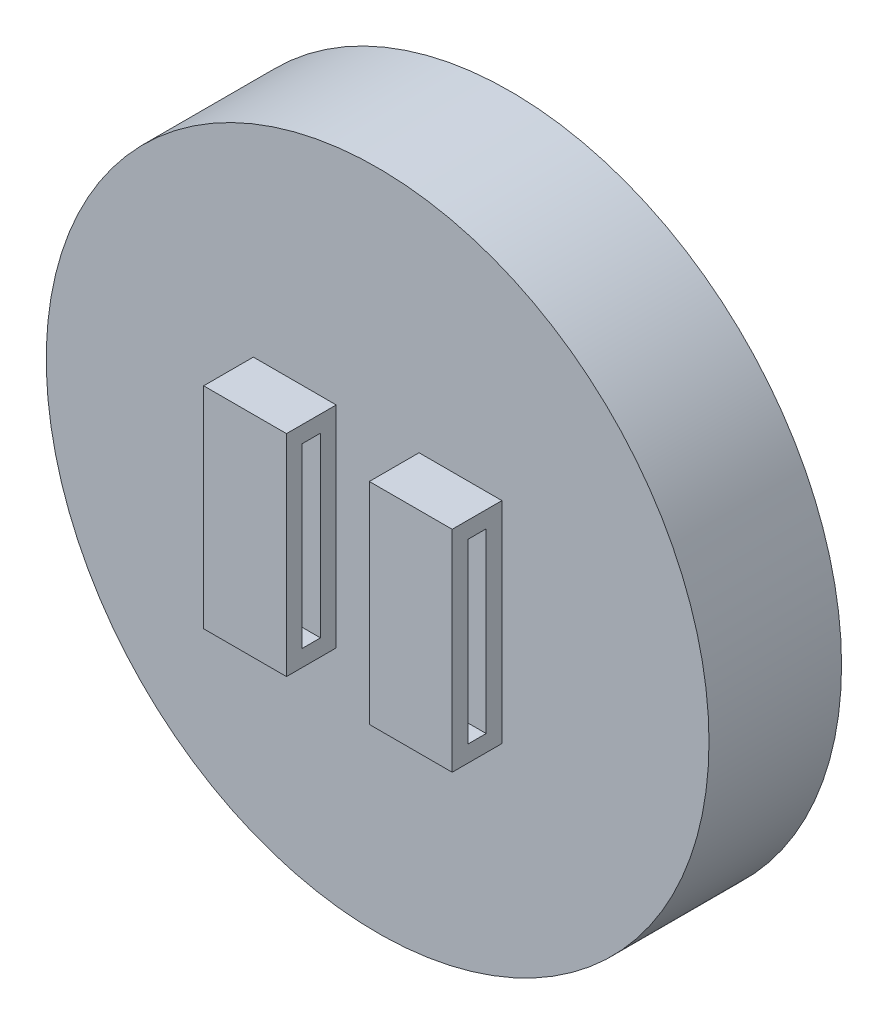
SolidWorks part; units mm, degrees
ref_plane "Front Plane" through (0, 0, 0) normal (0, 0, 1) x (1, 0, 0)
ref_plane "Top Plane" through (0, 0, 0) normal (0, 1, 0) x (1, 0, 0)
ref_plane "Right Plane" through (0, 0, 0) normal (1, 0, 0) x (0, 0, -1)
sketch "Sketch1" plane through (0, 0, 0) normal (0, 0, 1) x (1, 0, 0)
  circle A0 centre (0, 0) radius 20
extrude "Boss-Extrude1" add sketch "Sketch1" along normal blind 8
sketch "Sketch2" plane through (0, 0, 0) normal (0, 0, -1) x (-1, 0, 0)
  circle A0 centre (0, 0) radius 16
extrude "Cut-Extrude1" cut sketch "Sketch2" against normal blind 6.35
sketch "Sketch3" plane through (0, 0, 8) normal (0, 0, 1) x (1, 0, 0)
  line L0 (0, 0) -> (10, 0)
  line L1 (0, 0) -> (-10, 0)
  line L2 (-10, 0) -> (0, 0)
  line L3 (0, 0) -> (10, 0)
  line L5 (-7.5, -6.35) -> (-2.5, -6.35)
  line L6 (-7.5, -6.35) -> (-7.5, 6.35)
  line L7 (-7.5, 6.35) -> (-2.5, 6.35)
  line L8 (-2.5, -6.35) -> (-2.5, 6.35)
  line L9 (-7.5, -6.35) -> (-2.5, 6.35) construction
  line L10 (-7.5, 6.35) -> (-2.5, -6.35) construction
  line L11 (2.5, -6.35) -> (7.5, -6.35)
  line L12 (2.5, -6.35) -> (2.5, 6.35)
  line L13 (2.5, 6.35) -> (7.5, 6.35)
  line L14 (7.5, -6.35) -> (7.5, 6.35)
  line L15 (2.5, -6.35) -> (7.5, 6.35) construction
  line L16 (2.5, 6.35) -> (7.5, -6.35) construction
  point P1 (-5, 0)
  point P10 (5, 0)
  dimension "D1" = 5
  dimension "D2" = 5
  dimension "D3" = 12.7
  dimension "D4" = 12.7
extrude "Boss-Extrude2" add sketch "Sketch3" along normal blind 3 contours L5 L8 L2 L6 | L2 L8 L7 L6 | L3 L14 L13 L12 | L11 L14 L3 L12
ref_plane "Plane1" through (7.5, 6.35, 11) normal (0, 1, 0) x (1, 0, 0)
sketch "Sketch6" plane through (-7.5, 0, 0) normal (-1, 0, 0) x (0, 0, 1)
  line L0 (11, -6.35) -> (8, 6.35)
  line L2 (8.95, -5.35) -> (10.05, -5.35)
  line L3 (8.95, -5.35) -> (8.95, 5.35)
  line L4 (8.95, 5.35) -> (10.05, 5.35)
  line L5 (10.05, -5.35) -> (10.05, 5.35)
  line L6 (8.95, -5.35) -> (10.05, 5.35) construction
  line L7 (8.95, 5.35) -> (10.05, -5.35) construction
  point P4 (9.5, 0)
  dimension "D1" = 1.1
  dimension "D2" = 10.7
extrude "Cut-Extrude2" cut sketch "Sketch6" against normal blind 177.8 contours L2 L5 L0 L3 | L0 L5 L4 L3
